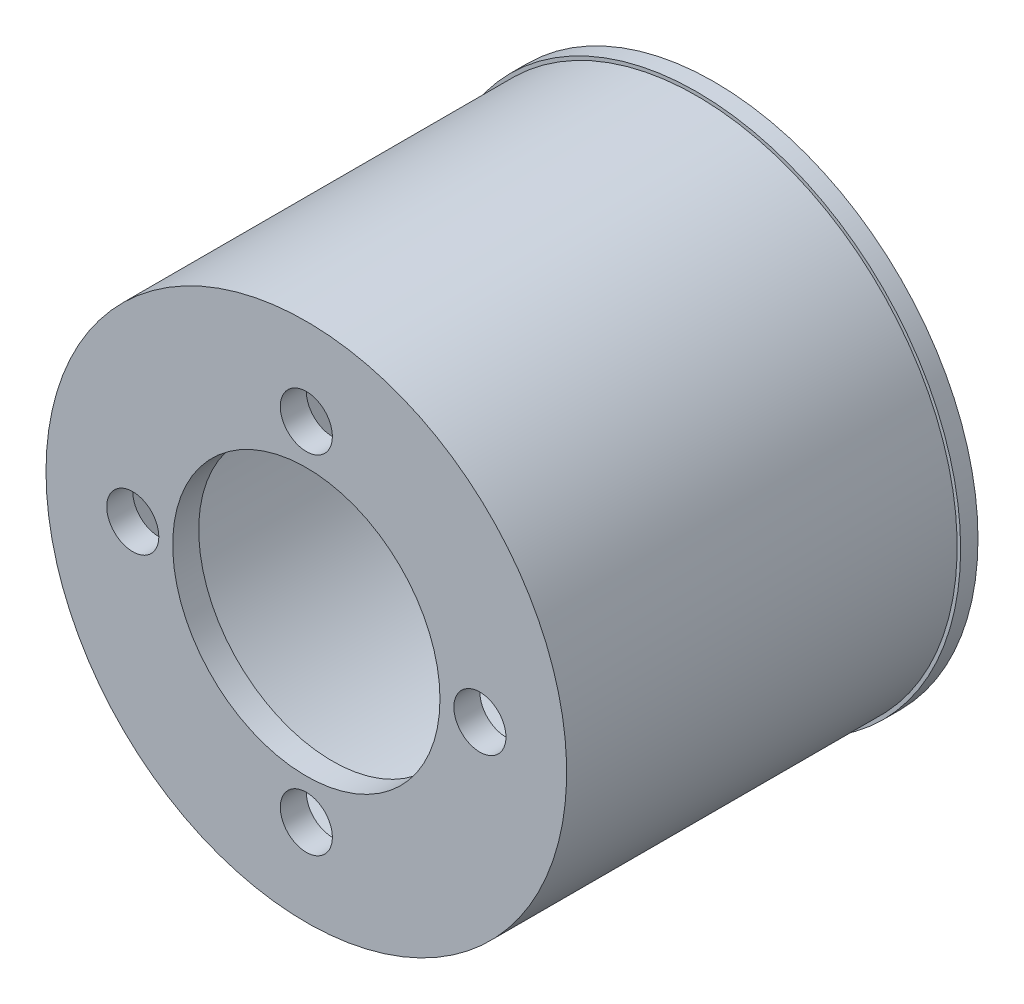
SolidWorks part; units mm, degrees
ref_plane "Plan de face" through (0, 0, 0) normal (0, 0, 1) x (1, 0, 0)
ref_plane "Plan de dessus" through (0, 0, 0) normal (0, 1, 0) x (1, 0, 0)
ref_plane "Plan de droite" through (0, 0, 0) normal (1, 0, 0) x (0, 0, -1)
sketch "Esquisse1" plane through (0, 0, 0) normal (0, 0, 1) x (1, 0, 0)
  circle A0 centre (0, 0) radius 13.35
  circle A1 centre (0, 0) radius 15
  dimension "D1" = 26.7
  dimension "D2" = 30
extrude "Boss.-Extru.1" add sketch "Esquisse1" along normal blind 21
sketch "Esquisse2" plane through (0, 0, 0) normal (0, 0, -1) x (-1, 0, 0)
  circle A0 centre (0, 0) radius 13.35
  circle A1 centre (0, 0) radius 15.2
  circle A2 centre (0, 0) radius 13.35 construction
  circle A3 centre (0, 0) radius 15 construction
  dimension "D1" = 0.2
extrude "Boss.-Extru.2" add sketch "Esquisse2" along normal blind 1
sketch "Esquisse3" plane through (0, 0, 21) normal (0, 0, 1) x (1, 0, 0)
  line L0 (0, -25.5382) -> (0, 31.1193) construction
  line L1 (-22.3718, 0) -> (24.0684, 0) construction
  circle A0 centre (0, 0) radius 15
  circle A1 centre (0, 0) radius 7.7
  circle A2 centre (0, 0) radius 15 construction
  circle A3 centre (0, -10) radius 1.5
  circle A4 centre (0, 10) radius 1.5
  circle A5 centre (-10, 0) radius 1.5
  circle A6 centre (10, 0) radius 1.5
  dimension "D1" = 15.4
  dimension "D2" = 10
  dimension "D4" = 3
  dimension "D3" = 10
  dimension "D5" = 10
  dimension "D6" = 10
extrude "Boss.-Extru.3" add sketch "Esquisse3" along normal blind 1.5
